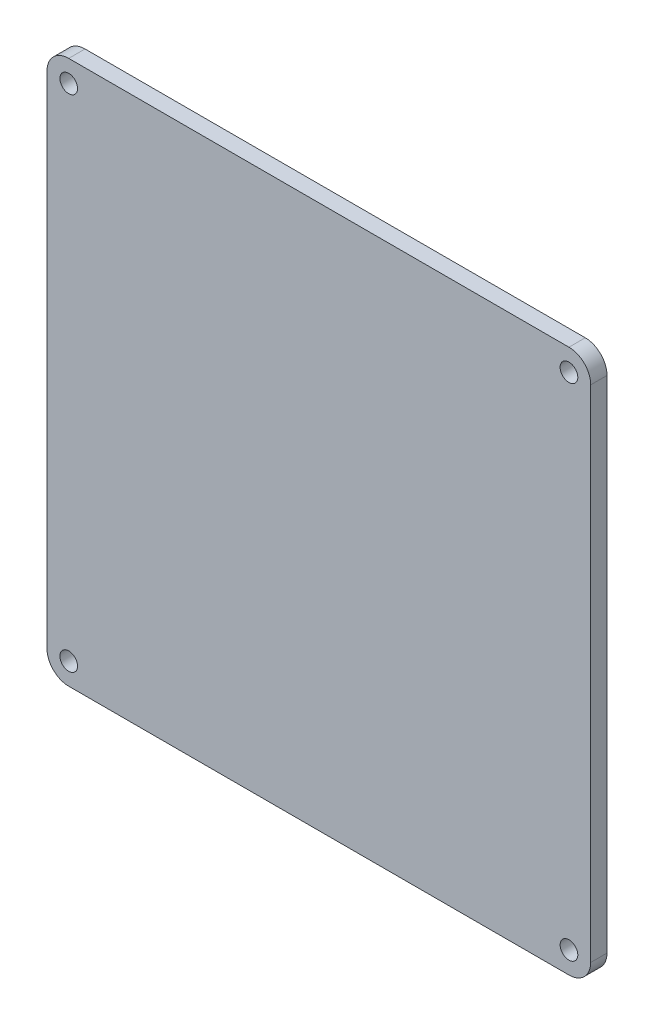
SolidWorks part; units mm, degrees
ref_plane "Ön Düzlem" through (0, 0, 0) normal (0, 0, 1) x (1, 0, 0)
ref_plane "Üst Düzlem" through (0, 0, 0) normal (0, 1, 0) x (1, 0, 0)
ref_plane "Sağ Düzlem" through (0, 0, 0) normal (1, 0, 0) x (0, 0, -1)
sketch "Çizim1" plane through (0, 0, 0) normal (0, 0, 1) x (1, 0, 0)
  line L1 (52.2796, -36.6022) -> (-47.7204, -36.6022)
  line L2 (52.2796, -36.6022) -> (52.2796, 63.3978)
  line L3 (52.2796, 63.3978) -> (-47.7204, 63.3978)
  line L4 (-47.7204, -36.6022) -> (-47.7204, 63.3978)
  point P0 (0, -2.7116)
  dimension "D1" = 100
  dimension "D2" = 100
extrude "Yükseklik-Ekstrüzyon1" add sketch "Çizim1" along normal blind 3
fillet "Radyus1" radius 4 4 edges at (52.2796, -36.6022, 1.5) (52.2796, 63.3978, 1.5) (-47.7204, 63.3978, 1.5) (-47.7204, -36.6022, 1.5)
sketch "Çizim12" plane through (0, 0, 0) normal (0, 0, -1) x (-1, 0, 0)
  circle A0 centre (-48.2796, 59.3978) radius 1.625
  circle A1 centre (43.7204, 59.3978) radius 1.625
  circle A2 centre (43.7204, -32.6022) radius 1.625
  circle A3 centre (-48.2796, -32.6022) radius 1.625
  dimension "D1" = 3.25
  dimension "D2" = 3.25
  dimension "D3" = 3.25
  dimension "D4" = 3.25
extrude "Kes-Ekstrüzyon7" cut sketch "Çizim12" against normal through all
